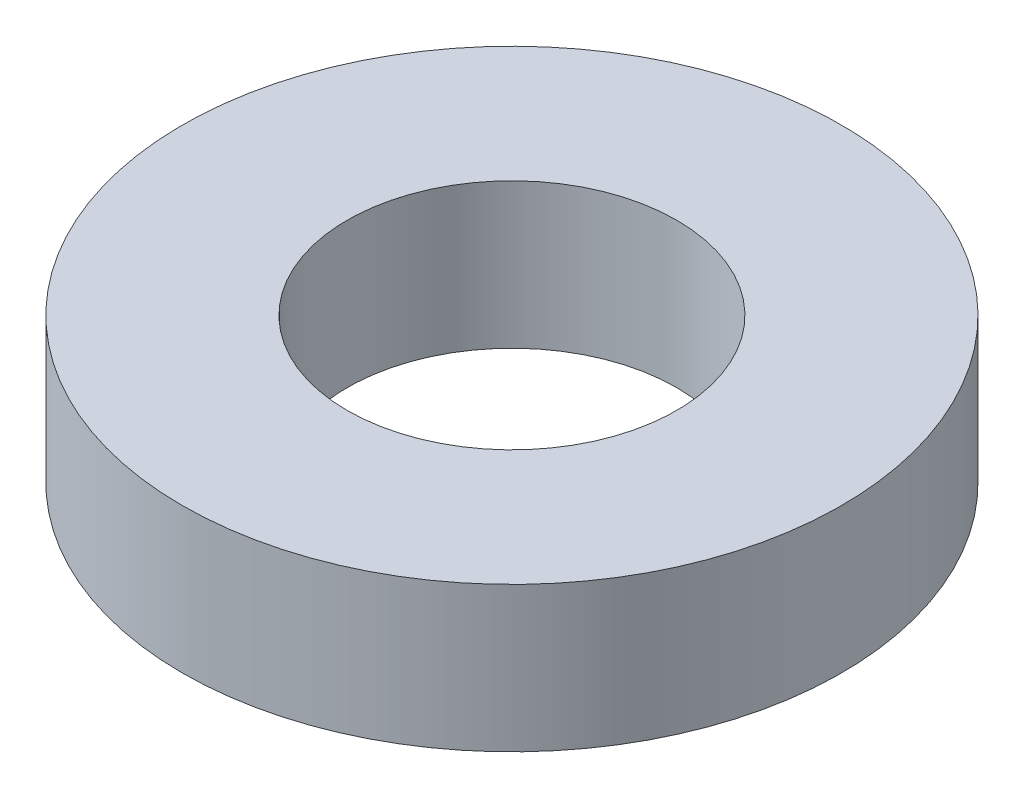
SolidWorks part; units mm, degrees
material "ABS PC"
ref_plane "Front Plane" through (0, 0, 0) normal (0, 0, 1) x (1, 0, 0)
ref_plane "Top Plane" through (0, 0, 0) normal (0, 1, 0) x (1, 0, 0)
ref_plane "Right Plane" through (0, 0, 0) normal (1, 0, 0) x (0, 0, -1)
sketch "Sketch1" plane through (0, 0, 0) normal (0, 1, 0) x (1, 0, 0)
  circle A0 centre (0, 0) radius 1.5
  circle A1 centre (0, 0) radius 3
  dimension "D1" = 3
  dimension "D2" = 6
extrude "Boss-Extrude1" add sketch "Sketch1" along normal mid plane 1.32
